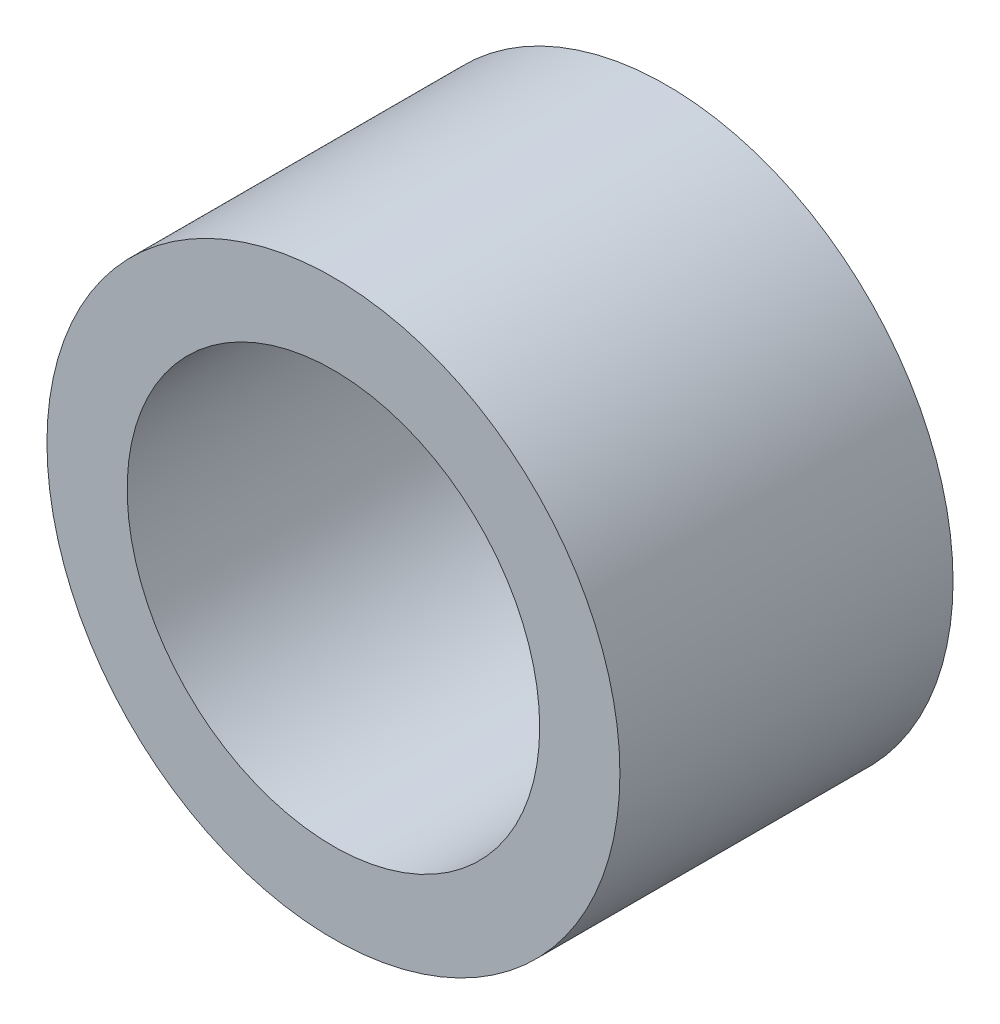
SolidWorks part; units mm, degrees
material "6061-T6 (SS)"
ref_plane "Front Plane" through (0, 0, 0) normal (0, 0, 1) x (1, 0, 0)
ref_plane "Top Plane" through (0, 0, 0) normal (0, 1, 0) x (1, 0, 0)
ref_plane "Right Plane" through (0, 0, 0) normal (1, 0, 0) x (0, 0, -1)
sketch "Sketch1" plane through (0, 0, 0) normal (1, 0, 0) x (0, 0, -1)
  line L0 (0, 4.445) -> (0, 0) construction
  line L1 (0, 3.2004) -> (5.1689, 3.2004)
  line L2 (0, 3.2004) -> (0, 4.445)
  line L3 (0, 4.445) -> (5.1689, 4.445)
  line L4 (5.1689, 3.2004) -> (5.1689, 4.445)
  line L5 (0, 3.2004) -> (5.1689, 4.445) construction
  line L6 (0, 4.445) -> (5.1689, 3.2004) construction
  line L7 (0, 0) -> (4.6181, 0) construction
  point P4 (2.5845, 3.8227)
  dimension "D1" = 3.2004
  dimension "D2" = 4.445
  dimension "D3" = 5.1689
revolve "Revolve1" add sketch "Sketch1" angle 360 about L7
